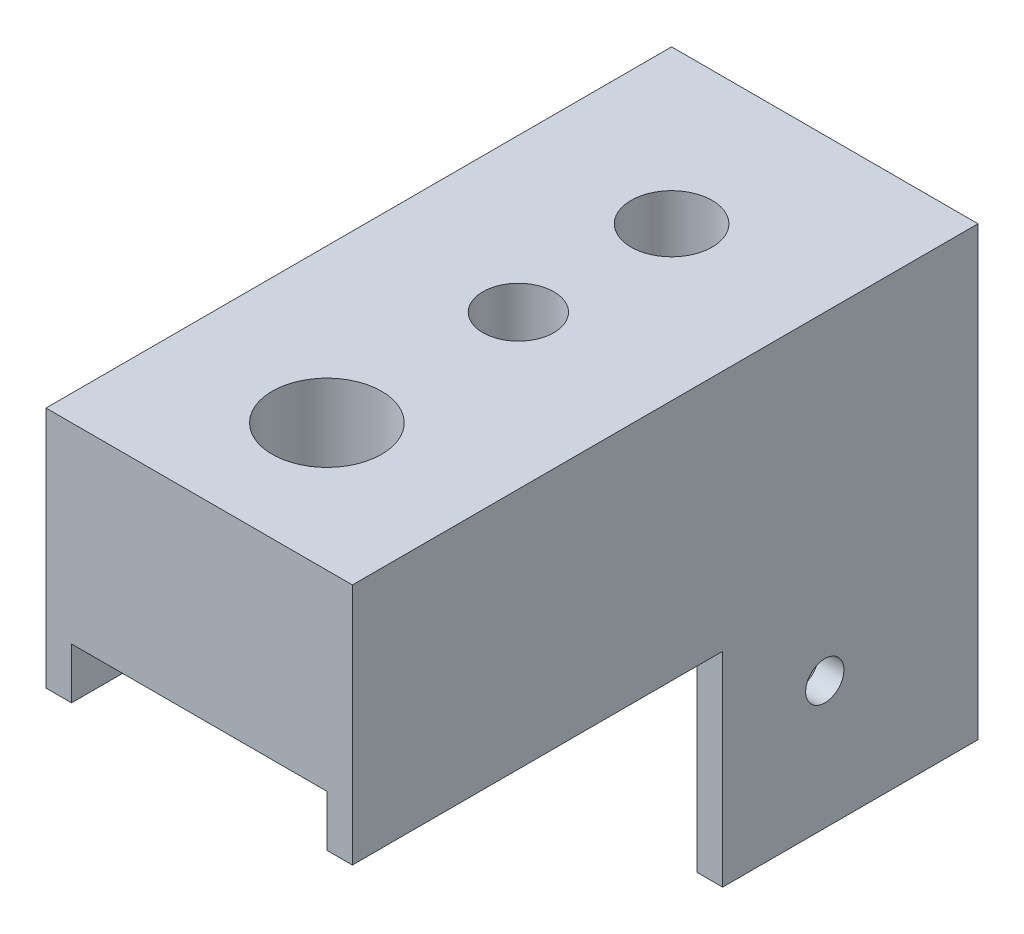
SolidWorks part; units mm, degrees
ref_plane "Front Plane" through (0, 0, 0) normal (0, 0, 1) x (1, 0, 0)
ref_plane "Top Plane" through (0, 0, 0) normal (0, 1, 0) x (1, 0, 0)
ref_plane "Right Plane" through (0, 0, 0) normal (1, 0, 0) x (0, 0, -1)
sketch "Sketch2" plane through (0, 0, 0) normal (1, 0, 0) x (0, 0, -1)
  line L0 (-44, 0) -> (0, 0)
  line L1 (0, 0) -> (0, -20)
  line L2 (-44, 0) -> (-44, 15)
  line L3 (-44, 15) -> (5, 15)
  line L4 (5, 15) -> (5, -20)
  line L5 (5, -20) -> (0, -20)
  dimension "D1" = 20
  dimension "D2" = 44
  dimension "D3" = 5
  dimension "D4" = 15
extrude "Boss-Extrude1" add sketch "Sketch2" along normal mid plane 20
sketch "Sketch3" plane through (10, 0, 0) normal (1, 0, 0) x (0, 0, -1)
  line L0 (-44, 15) -> (-44, -4)
  line L1 (-44, -4) -> (-15, -4)
  line L2 (-15, -4) -> (-15, -20)
  line L3 (-15, -20) -> (5, -20)
  line L6 (-44, 15) -> (5, 15)
  line L7 (5, 15) -> (5, -20)
  line L8 (0, 0) -> (0, -20) construction
  line L9 (-44, 0) -> (0, 0) construction
  dimension "D1" = 15
  dimension "D2" = 4
extrude "Boss-Extrude2" add sketch "Sketch3" along normal blind 2
mirror "Mirror1" about plane through (0, 0, 0) normal (1, 0, 0) of "Boss-Extrude2"
sketch "Sketch4" plane through (0, 0, 0) normal (0, -1, 0) x (1, 0, 0)
  line L0 (0, 0) -> (0, 7) construction
  line L1 (10, 0) -> (-10, 0) construction
  line L2 (0, 7) -> (0, 19) construction
  line L3 (0, 19) -> (0, 34) construction
  circle A0 centre (0, 34) radius 4.285
  circle A1 centre (0, 19) radius 2.78
  circle A2 centre (0, 7) radius 3.175
  dimension "D1" = 8.57
  dimension "D5" = 5.56
  dimension "D6" = 6.35
  dimension "D2" = 7
  dimension "D3" = 12
  dimension "D4" = 15
extrude "Cut-Extrude1" cut sketch "Sketch4" against normal through all
sketch "Sketch5" plane through (12, 0, -12) normal (-1, 0, 0) x (0, 0, 1)
  line L0 (19, -10) -> (19, -20) construction
  line L2 (27, -20) -> (7, -20) construction
  line L3 (7, -20) -> (7, 15) construction
  circle A0 centre (19, -10) radius 1.5
  point P2 (14.0267, -20)
  dimension "D2" = 3
  dimension "D1" = 10
  dimension "D3" = 12
extrude "Cut-Extrude2" cut sketch "Sketch5" along normal through all
